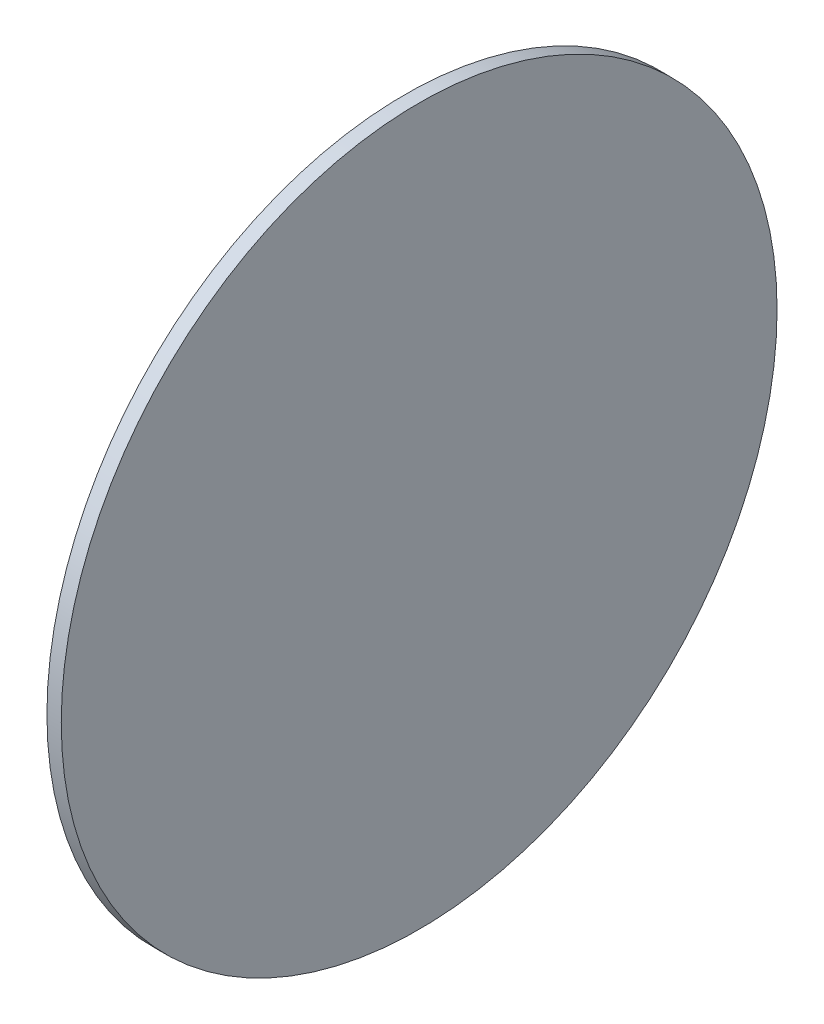
SolidWorks part; units mm, degrees
material "Pin"
ref_plane "Plan de face" through (0, 0, 0) normal (0, 0, 1) x (1, 0, 0)
ref_plane "Plan de dessus" through (0, 0, 0) normal (0, 1, 0) x (1, 0, 0)
ref_plane "Plan de droite" through (0, 0, 0) normal (1, 0, 0) x (0, 0, -1)
sketch "Esquisse2" plane through (0, 0, 0) normal (1, 0, 0) x (0, 0, -1)
  circle A0 centre (0, 0) radius 500
  dimension "D1" = 1000
extrude "Boss.-Extru.2" add sketch "Esquisse2" along normal blind 20
